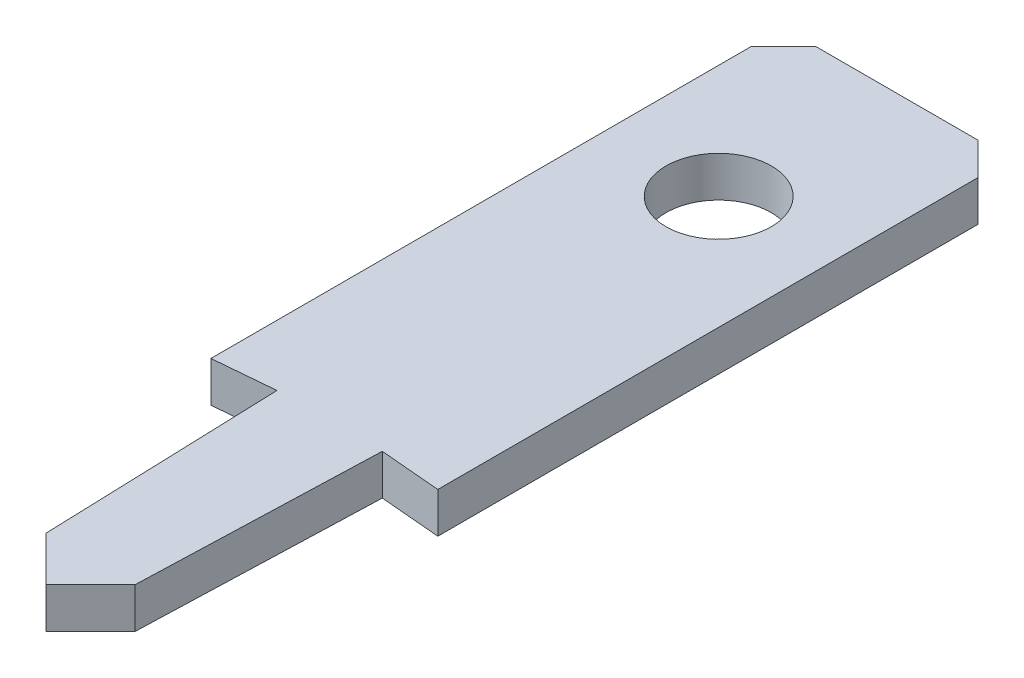
SolidWorks part; units mm, degrees
ref_plane "Front Plane" through (0, 0, 0) normal (0, 0, 1) x (1, 0, 0)
ref_plane "Top Plane" through (0, 0, 0) normal (0, 1, 0) x (1, 0, 0)
ref_plane "Right Plane" through (0, 0, 0) normal (1, 0, 0) x (0, 0, -1)
sketch "Sketch1" plane through (0, 0, 0) normal (0, 1, 0) x (1, 0, 0)
  line L0 (0, 37.1961) -> (0, -27.8261) construction
  line L1 (-1, 7) -> (1, 7)
  line L2 (1.4, 6.6) -> (1, 7)
  line L3 (1.4, 6.6) -> (1.4, -0.0656)
  line L4 (1.4, -0.0656) -> (0.65, 0)
  line L5 (0.65, 0) -> (0.55, -2.95)
  line L6 (0.55, -2.95) -> (0, -3.5)
  line L7 (-7.8909, 0) -> (27.5832, 0) construction
  line L8 (-1.2661, -3.5) -> (7.0361, -3.5) construction
  line L9 (-0.55, -2.95) -> (0, -3.5)
  line L10 (-0.65, 0) -> (-0.55, -2.95)
  line L11 (-1.4, -0.0656) -> (-0.65, 0)
  line L12 (-1.4, 6.6) -> (-1.4, -0.0656)
  line L13 (-1.4, 6.6) -> (-1, 7)
  point P19 (0, 7)
  dimension "D1" = 5
  dimension "D2" = 45
  dimension "D3" = 1.4
  dimension "D4" = 0.55
  dimension "D5" = 45
  dimension "D6" = 10.5
  dimension "D7" = 7
  dimension "D8" = 0.65
  dimension "D9" = 1
extrude "Boss-Extrude2" add sketch "Sketch1" along normal blind 0.5
sketch "Sketch3" plane through (0, 0.5, 0) normal (0, 1, 0) x (1, 0, 0)
  line L0 (1, 7) -> (-1, 7) construction
  circle A0 centre (0, 4.8) radius 0.65
  dimension "D1" = 1.3
  dimension "D2" = 2.2
extrude "Cut-Extrude3" cut sketch "Sketch3" against normal blind 0.5
